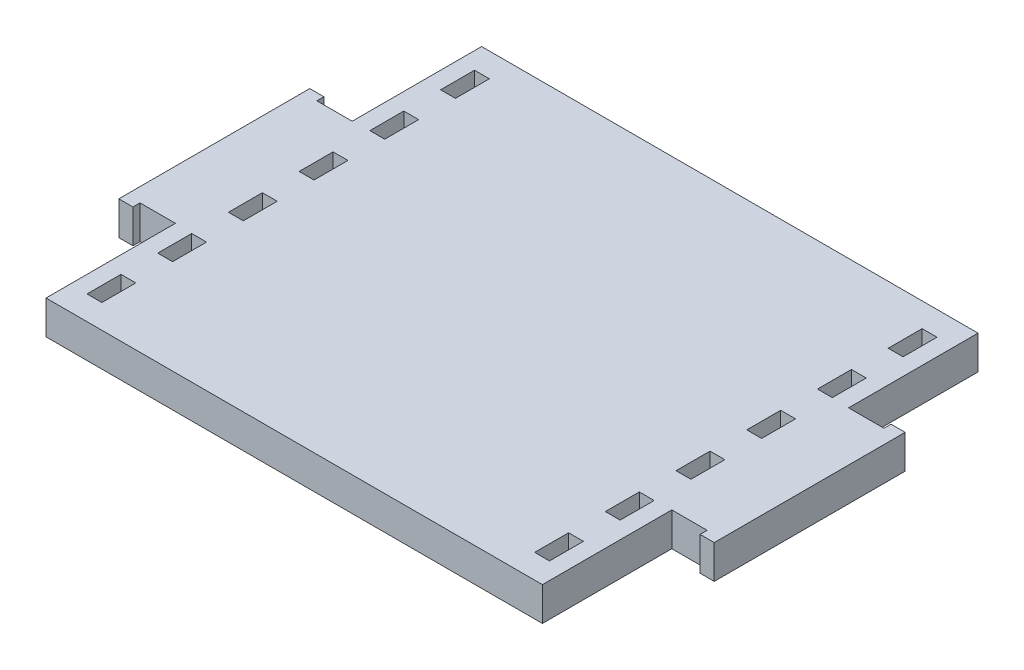
SolidWorks part; units mm, degrees
ref_plane "Front Plane" through (0, 0, 0) normal (0, 0, 1) x (1, 0, 0)
ref_plane "Top Plane" through (0, 0, 0) normal (0, 1, 0) x (1, 0, 0)
ref_plane "Right Plane" through (0, 0, 0) normal (1, 0, 0) x (0, 0, -1)
sketch "Sketch1" plane through (0, 0, 0) normal (0, 1, 0) x (1, 0, 0)
  line L0 (0, 39.116) -> (0, -39.116) construction
  line L1 (-44.577, 39.116) -> (44.577, 39.116)
  line L2 (-44.577, 39.116) -> (-44.577, -39.116)
  line L3 (-44.577, -39.116) -> (44.577, -39.116)
  line L4 (44.577, 39.116) -> (44.577, -39.116)
  line L5 (-44.577, 15.875) -> (-50.927, 15.875)
  line L6 (-44.577, 15.875) -> (-44.577, -15.875)
  line L7 (-44.577, -15.875) -> (-50.927, -15.875)
  line L8 (-50.927, 15.875) -> (-50.927, -15.875)
  line L9 (44.577, -15.875) -> (50.927, -15.875)
  line L10 (50.927, 15.875) -> (50.927, -15.875)
  line L11 (44.577, 15.875) -> (50.927, 15.875)
  line L12 (44.577, 15.875) -> (44.577, -15.875)
  point P4 (0, 39.116)
  point P6 (-44.577, 0)
  point P11 (-50.927, 0)
  dimension "D1" = 89.154
  dimension "D2" = 78.232
  dimension "D3" = 6.35
  dimension "D4" = 31.75
extrude "Boss-Extrude1" add sketch "Sketch1" along normal mid plane 6.0452 contours L0 L1 L2 L3 | L5 L8 L7 L2 | L1 L0 L3 L4 | L11 L4 L9 L10
sketch "Sketch4" plane through (0, 3.0226, 0) normal (0, 1, 0) x (1, 0, 0)
  line L0 (-41.529, -34.798) -> (-38.862, -34.798)
  line L1 (-41.529, -34.798) -> (-41.529, -28.702)
  line L2 (-41.529, -28.702) -> (-38.862, -28.702)
  line L3 (-38.862, -34.798) -> (-38.862, -28.702)
  line L4 (-44.577, -15.875) -> (-44.577, -39.116) construction
  line L5 (-44.577, -39.116) -> (44.577, -39.116) construction
  line L6 (-41.529, -22.098) -> (-38.862, -22.098)
  line L7 (-38.862, -22.098) -> (-38.862, -16.002)
  line L8 (-41.529, -16.002) -> (-38.862, -16.002)
  line L9 (-41.529, -22.098) -> (-41.529, -16.002)
  line L10 (-41.529, -9.398) -> (-38.862, -9.398)
  line L11 (-38.862, -9.398) -> (-38.862, -3.302)
  line L12 (-41.529, -3.302) -> (-38.862, -3.302)
  line L13 (-41.529, -9.398) -> (-41.529, -3.302)
  line L14 (-41.529, 3.302) -> (-38.862, 3.302)
  line L15 (-38.862, 3.302) -> (-38.862, 9.398)
  line L16 (-41.529, 9.398) -> (-38.862, 9.398)
  line L17 (-41.529, 3.302) -> (-41.529, 9.398)
  line L18 (-41.529, 16.002) -> (-38.862, 16.002)
  line L19 (-38.862, 16.002) -> (-38.862, 22.098)
  line L20 (-41.529, 22.098) -> (-38.862, 22.098)
  line L21 (-41.529, 16.002) -> (-41.529, 22.098)
  line L22 (-41.529, 28.702) -> (-38.862, 28.702)
  line L23 (-38.862, 28.702) -> (-38.862, 34.798)
  line L24 (-41.529, 34.798) -> (-38.862, 34.798)
  line L25 (-41.529, 28.702) -> (-41.529, 34.798)
  line L26 (38.862, -22.098) -> (41.529, -22.098)
  line L27 (41.529, -22.098) -> (41.529, -16.002)
  line L28 (38.862, -16.002) -> (41.529, -16.002)
  line L29 (38.862, -22.098) -> (38.862, -16.002)
  line L30 (38.862, -9.398) -> (41.529, -9.398)
  line L31 (41.529, -9.398) -> (41.529, -3.302)
  line L32 (38.862, -3.302) -> (41.529, -3.302)
  line L33 (38.862, -9.398) -> (38.862, -3.302)
  line L34 (38.862, 3.302) -> (41.529, 3.302)
  line L35 (41.529, 3.302) -> (41.529, 9.398)
  line L36 (38.862, 9.398) -> (41.529, 9.398)
  line L37 (38.862, 3.302) -> (38.862, 9.398)
  line L38 (38.862, 16.002) -> (41.529, 16.002)
  line L39 (41.529, 16.002) -> (41.529, 22.098)
  line L40 (38.862, 22.098) -> (41.529, 22.098)
  line L41 (38.862, 16.002) -> (38.862, 22.098)
  line L42 (38.862, 28.702) -> (41.529, 28.702)
  line L43 (41.529, 28.702) -> (41.529, 34.798)
  line L44 (38.862, 34.798) -> (41.529, 34.798)
  line L45 (38.862, 28.702) -> (38.862, 34.798)
  line L46 (38.862, -34.798) -> (41.529, -34.798)
  line L47 (41.529, -34.798) -> (41.529, -28.702)
  line L48 (38.862, -28.702) -> (41.529, -28.702)
  line L49 (38.862, -34.798) -> (38.862, -28.702)
  line L50 (-41.529, -34.798) -> (-41.529, -22.098) construction
  line L51 (-41.529, -34.798) -> (38.862, -34.798) construction
  dimension "D1" = 6.096
  dimension "D2" = 2.667
  dimension "D3" = 3.048
  dimension "D4" = 4.318
  dimension "D5" = 12.7
  dimension "D6" = 80.391
  dimension "D7" = 6
  dimension "D8" = 2
extrude "Cut-Extrude2" cut sketch "Sketch4" against normal blind 6.0452
sketch "Sketch5" plane through (0, 3.0226, 0) normal (0, 1, 0) x (1, 0, 0)
  line L0 (-50.927, 15.875) -> (-50.927, -15.875) construction
  line L1 (-53.467, 17.145) -> (-50.927, 17.145)
  line L2 (-53.467, 17.145) -> (-53.467, -17.145)
  line L3 (-53.467, -17.145) -> (-50.927, -17.145)
  line L4 (-50.927, 17.145) -> (-50.927, -17.145)
  line L8 (0, 39.116) -> (0, -39.116) construction
  line L9 (-44.577, 39.116) -> (44.577, 39.116) construction
  line L10 (-44.577, -39.116) -> (44.577, -39.116) construction
  line L11 (53.467, -17.145) -> (50.927, -17.145)
  line L12 (50.927, 17.145) -> (50.927, -17.145)
  line L13 (53.467, 17.145) -> (50.927, 17.145)
  line L14 (53.467, 17.145) -> (53.467, -17.145)
  line L15 (-44.577, 15.875) -> (-50.927, 15.875) construction
  point P6 (-53.467, 0)
  dimension "D1" = 1.27
  dimension "D2" = 2.54
extrude "Boss-Extrude2" add sketch "Sketch5" against normal blind 6.0452
